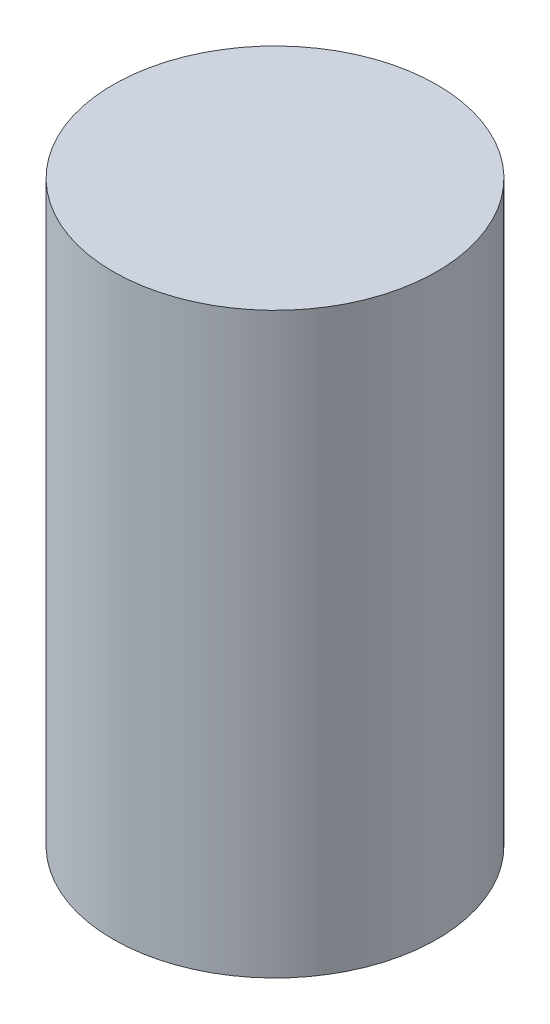
SolidWorks part; units mm, degrees
ref_plane "Front Plane" through (0, 0, 0) normal (0, 0, 1) x (1, 0, 0)
ref_plane "Top Plane" through (0, 0, 0) normal (0, 1, 0) x (1, 0, 0)
ref_plane "Right Plane" through (0, 0, 0) normal (1, 0, 0) x (0, 0, -1)
sketch "Sketch1" plane through (0, 0, 0) normal (0, 1, 0) x (1, 0, 0)
  circle A0 centre (0, 0) radius 10.668
  dimension "D1" = 21.336
extrude "Boss-Extrude1" add sketch "Sketch1" along normal blind 38.1
